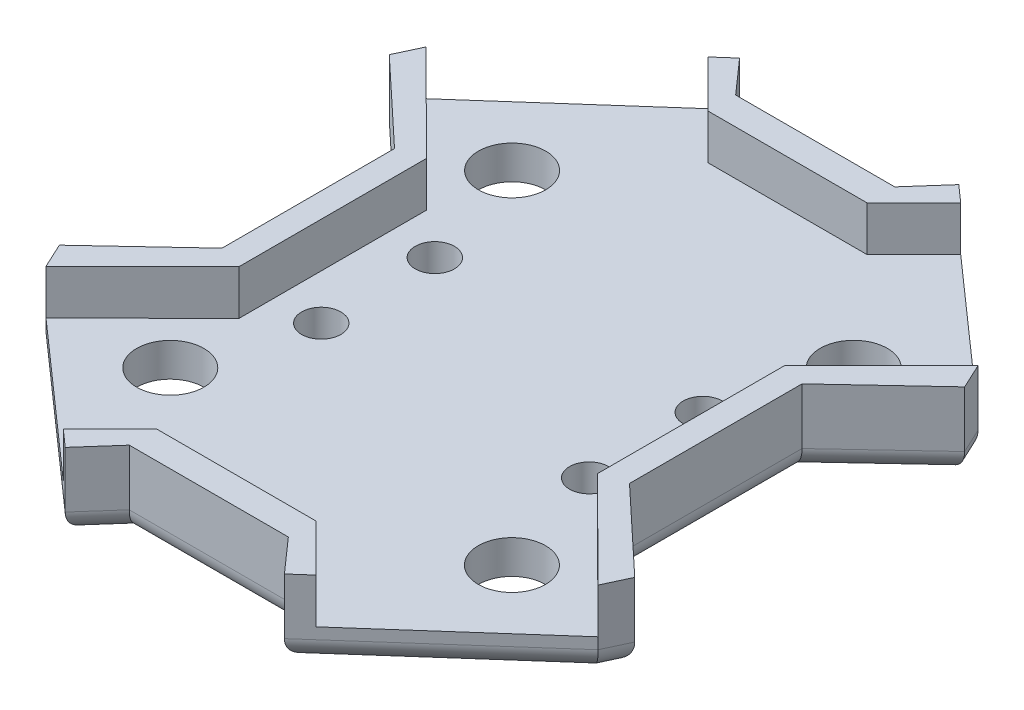
SolidWorks part; units mm, degrees
material "ABS"
ref_plane "Front Plane" through (0, 0, 0) normal (0, 0, 1) x (1, 0, 0)
ref_plane "Top Plane" through (0, 0, 0) normal (0, 1, 0) x (1, 0, 0)
ref_plane "Right Plane" through (0, 0, 0) normal (1, 0, 0) x (0, 0, -1)
sketch "Sketch1" plane through (0, 0, 0) normal (0, 1, 0) x (1, 0, 0)
  line L1 (27.5, -32.215) -> (-27.5, -32.215)
  line L2 (27.5, -32.215) -> (27.5, 32.215)
  line L3 (27.5, 32.215) -> (-27.5, 32.215)
  line L4 (-27.5, -32.215) -> (-27.5, 32.215)
  line L5 (27.5, -32.215) -> (-27.5, 32.215) construction
  line L6 (27.5, 32.215) -> (-27.5, -32.215) construction
  point P0 (0, 0)
  dimension "D1" = 64.43
  dimension "D2" = 55
extrude "Boss-Extrude1" add sketch "Sketch1" along normal blind 3
sketch "Sketch2" plane through (0, 3, 0) normal (0, 1, 0) x (1, 0, 0)
  line L0 (-27.5, -32.215) -> (-27.5, 0) construction
  line L1 (-27.5, 32.215) -> (-27.5, -32.215) construction
  line L2 (-27.5, -32.215) -> (0, -32.215) construction
  line L3 (-27.5, -32.215) -> (27.5, -32.215) construction
  line L4 (-27.5, -4.7913) -> (-27.5, -14.3738)
  line L5 (-27.5, 0) -> (-17.5, 0) construction
  line L6 (-27.5, 4.7913) -> (-27.5, -4.7913)
  line L8 (-17.5, 5) -> (-17.5, -5)
  line L9 (-27.5, -14.3738) -> (-17.5, -5)
  line L10 (0, -32.215) -> (0, 32.215) construction
  line L11 (27.5, 32.215) -> (-27.5, 32.215) construction
  line L12 (-27.5, 14.3738) -> (-17.5, 5)
  line L13 (-27.5, 4.7913) -> (-27.5, 14.3738)
  line L14 (27.5, 4.7913) -> (27.5, 14.3738)
  line L15 (27.5, 14.3738) -> (17.5, 5)
  line L16 (27.5, 4.7913) -> (27.5, -4.7913)
  line L17 (27.5, 0) -> (17.5, 0) construction
  line L18 (17.5, 5) -> (17.5, -5)
  line L19 (27.5, -14.3738) -> (17.5, -5)
  line L20 (27.5, -4.7913) -> (27.5, -14.3738)
  dimension "D1" = 10
  dimension "D2" = 5
extrude "Cut-Extrude1" cut sketch "Sketch2" against normal blind 4
sketch "Sketch3" plane through (0, 3, 0) normal (0, 1, 0) x (1, 0, 0)
  line L0 (-27.5, 14.3738) -> (27.5, 14.3738) construction
  line L1 (0, -32.215) -> (0, 32.215) construction
  line L2 (-27.5, -32.215) -> (27.5, -32.215) construction
  line L3 (27.5, 32.215) -> (-27.5, 32.215) construction
  line L4 (-17.5, 0) -> (17.5, 0) construction
  line L5 (-17.5, -5) -> (-17.5, 5) construction
  line L6 (17.5, 5) -> (17.5, -5) construction
  line L7 (-27.5, 14.3738) -> (-25.8679, 17.8738)
  line L8 (-17.5, 5) -> (-17.5, 0)
  line L9 (-25.8679, 17.8738) -> (27.5, 17.8738) construction
  line L10 (27.5, 14.3738) -> (27.5, 32.215) construction
  line L11 (-25.8679, 17.8738) -> (-25.8679, 32.215) construction
  line L12 (-25.8679, 17.8738) -> (-9.6529, 32.215)
  line L13 (-9.6529, 32.215) -> (-3.7424, 25.5322)
  line L14 (-3.7424, 25.5322) -> (3.7424, 25.5322)
  line L15 (9.6529, 32.215) -> (3.7424, 25.5322)
  line L16 (25.8679, 17.8738) -> (9.6529, 32.215)
  line L17 (27.5, 14.3738) -> (25.8679, 17.8738)
  line L27 (-17.5, 5) -> (-27.5, 14.3738)
  line L30 (17.5, 5) -> (27.5, 14.3738)
  line L31 (17.5, 5) -> (17.5, -5)
  line L32 (17.5, -5) -> (27.5, -14.3738)
  line L33 (27.5, -14.3738) -> (25.8679, -17.8738)
  line L34 (25.8679, -17.8738) -> (9.6529, -32.215)
  line L35 (9.6529, -32.215) -> (3.7424, -25.5322)
  line L36 (-3.7424, -25.5322) -> (3.7424, -25.5322)
  line L37 (-9.6529, -32.215) -> (-3.7424, -25.5322)
  line L38 (-25.8679, -17.8738) -> (-9.6529, -32.215)
  line L39 (-27.5, -14.3738) -> (-25.8679, -17.8738)
  line L40 (-17.5, -5) -> (-27.5, -14.3738)
  line L41 (-17.5, -5) -> (-17.5, 0)
  line L42 (-16, -5.6499) -> (-16, 0)
  line L43 (-16, 5.6499) -> (-16, 0)
  line L44 (-16, 5.6499) -> (-25.6812, 14.7249)
  line L45 (-25.6812, 14.7249) -> (-24.6404, 16.957)
  line L46 (-24.6404, 16.957) -> (-9.7828, 30.0977)
  line L47 (-9.7828, 30.0977) -> (-4.4183, 24.0322)
  line L48 (-4.4183, 24.0322) -> (4.4183, 24.0322)
  line L49 (9.7828, 30.0977) -> (4.4183, 24.0322)
  line L50 (24.6404, 16.957) -> (9.7828, 30.0977)
  line L51 (25.6812, 14.7249) -> (24.6404, 16.957)
  line L52 (16, 5.6499) -> (25.6812, 14.7249)
  line L53 (16, 5.6499) -> (16, -5.6499)
  line L54 (16, -5.6499) -> (25.6812, -14.7249)
  line L55 (25.6812, -14.7249) -> (24.6404, -16.957)
  line L56 (24.6404, -16.957) -> (9.7828, -30.0977)
  line L57 (9.7828, -30.0977) -> (4.4183, -24.0322)
  line L58 (-4.4183, -24.0322) -> (4.4183, -24.0322)
  line L59 (-9.7828, -30.0977) -> (-4.4183, -24.0322)
  line L60 (-24.6404, -16.957) -> (-9.7828, -30.0977)
  line L61 (-25.6812, -14.7249) -> (-24.6404, -16.957)
  line L62 (-16, -5.6499) -> (-25.6812, -14.7249)
  point P27 (0, 23.6915)
  dimension "D1" = 1.5
  dimension "D2" = 3.5
extrude "Cut-Extrude4" cut sketch "Sketch3" against normal blind 4 flip side to cut contours L42 L43 L44 L45 L46 L47 L48 L49 L50 L51 L52 L53 L54 L55 L56 L57 L58 L59 L60 L61 L62
sketch "Sketch4" plane through (0, 3, 0) normal (0, 1, 0) x (1, 0, 0)
  line L0 (-7.1005, 27.0649) -> (7.1005, 27.0649)
  line L1 (-9.7828, 30.0977) -> (-4.4183, 24.0322) construction
  line L2 (9.7828, 30.0977) -> (4.4183, 24.0322) construction
  line L3 (-7.1005, -27.0649) -> (7.1005, -27.0649)
  line L4 (-9.7828, -30.0977) -> (-4.4183, -24.0322) construction
  line L5 (9.7828, -30.0977) -> (4.4183, -24.0322) construction
  line L6 (7.1005, -27.0649) -> (4.4183, -24.0322)
  line L7 (4.4183, -24.0322) -> (-4.4183, -24.0322)
  line L8 (-4.4183, -24.0322) -> (-7.1005, -27.0649)
  line L9 (-7.1005, 27.0649) -> (-4.4183, 24.0322)
  line L10 (-4.4183, 24.0322) -> (4.4183, 24.0322)
  line L11 (4.4183, 24.0322) -> (7.1005, 27.0649)
extrude "Boss-Extrude2" add sketch "Sketch4" against normal blind 3
sketch "Sketch5" plane through (0, 3, 0) normal (0, 1, 0) x (1, 0, 0)
  line L0 (-16, 5.6499) -> (-18.1887, 7.7016)
  line L1 (-16, 5.6499) -> (-25.6812, 14.7249) construction
  line L2 (-16, -5.6499) -> (-18.1887, -7.7016)
  line L3 (-16, -5.6499) -> (-25.6812, -14.7249) construction
  line L4 (-18.1887, 7.7016) -> (-18.1887, -7.7016)
  line L5 (-16, 5.6499) -> (-16, -5.6499)
  line L6 (0, 27.0649) -> (0, -27.0649) construction
  line L7 (7.1005, 27.0649) -> (-7.1005, 27.0649) construction
  line L8 (-7.1005, -27.0649) -> (7.1005, -27.0649) construction
  line L9 (16, 5.6499) -> (18.1887, 7.7016)
  line L10 (18.1887, 7.7016) -> (18.1887, -7.7016)
  line L11 (16, -5.6499) -> (18.1887, -7.7016)
  line L12 (16, 5.6499) -> (16, -5.6499)
  dimension "D1" = 3
  dimension "D2" = 3
extrude "Boss-Extrude3" add sketch "Sketch5" against normal blind 3
sketch "Sketch6" plane through (0, 3, 0) normal (0, 1, 0) x (1, 0, 0)
  line L0 (-24.6404, -16.957) -> (-25.6812, -14.7249)
  line L1 (-25.6812, -14.7249) -> (-18.1887, -7.7016)
  line L2 (-18.1887, -7.7016) -> (-18.1887, 7.7016)
  line L3 (-18.1887, 7.7016) -> (-25.6812, 14.7249)
  line L4 (-25.6812, 14.7249) -> (-24.6404, 16.957)
  line L5 (-24.6404, 16.957) -> (-16, 8.3734)
  line L6 (-16, 8.3734) -> (-16, -8.3734)
  line L7 (-16, -8.3734) -> (-24.6404, -16.957)
  line L8 (-18.1887, 7.7016) -> (-18.1887, -7.7016) construction
  line L9 (0, 27.0649) -> (0, -27.0649) construction
  line L10 (7.1005, 27.0649) -> (-7.1005, 27.0649) construction
  line L11 (-7.1005, -27.0649) -> (7.1005, -27.0649) construction
  line L12 (16, -8.3734) -> (24.6404, -16.957)
  line L13 (16, 8.3734) -> (16, -8.3734)
  line L14 (24.6404, 16.957) -> (16, 8.3734)
  line L15 (25.6812, 14.7249) -> (24.6404, 16.957)
  line L16 (18.1887, 7.7016) -> (25.6812, 14.7249)
  line L17 (18.1887, -7.7016) -> (18.1887, 7.7016)
  line L18 (25.6812, -14.7249) -> (18.1887, -7.7016)
  line L19 (24.6404, -16.957) -> (25.6812, -14.7249)
extrude "Boss-Extrude4" add sketch "Sketch6" along normal blind 4
sketch "Sketch7" plane through (0, 3, 0) normal (0, 1, 0) x (1, 0, 0)
  line L1 (-1, 27.0649) -> (-7.1005, 27.0649)
  line L2 (-7.1005, 27.0649) -> (-9.7828, 30.0977)
  line L3 (-9.7828, 30.0977) -> (-11.2809, 28.7727)
  line L4 (-1, 24.5949) -> (-7.1005, 24.5949)
  line L5 (-7.1005, 24.5949) -> (-11.2809, 28.7727)
  line L6 (0, 27.0649) -> (0, -27.0649) construction
  line L7 (7.1005, 27.0649) -> (-7.1005, 27.0649) construction
  line L8 (-7.1005, -27.0649) -> (7.1005, -27.0649) construction
  line L9 (-1, 27.0649) -> (1, 27.0649)
  line L10 (-1, 24.5949) -> (1, 24.5949)
  line L12 (1, 24.5949) -> (7.1005, 24.5949)
  line L13 (7.1005, 24.5949) -> (11.2809, 28.7727)
  line L14 (9.7828, 30.0977) -> (11.2809, 28.7727)
  line L15 (7.1005, 27.0649) -> (9.7828, 30.0977)
  line L16 (1, 27.0649) -> (7.1005, 27.0649)
  line L17 (-18.1887, 0) -> (18.1887, 0) construction
  line L18 (-18.1887, 7.7016) -> (-18.1887, -7.7016) construction
  line L19 (18.1887, -7.7016) -> (18.1887, 7.7016) construction
  line L20 (-1, -27.0649) -> (-7.1005, -27.0649)
  line L21 (-7.1005, -27.0649) -> (-9.7828, -30.0977)
  line L22 (-9.7828, -30.0977) -> (-11.2809, -28.7727)
  line L23 (-7.1005, -24.5949) -> (-11.2809, -28.7727)
  line L24 (-1, -24.5949) -> (-7.1005, -24.5949)
  line L25 (-1, -24.5949) -> (1, -24.5949)
  line L26 (1, -24.5949) -> (7.1005, -24.5949)
  line L27 (7.1005, -24.5949) -> (11.2809, -28.7727)
  line L28 (9.7828, -30.0977) -> (11.2809, -28.7727)
  line L29 (7.1005, -27.0649) -> (9.7828, -30.0977)
  line L30 (1, -27.0649) -> (7.1005, -27.0649)
  line L31 (-1, -27.0649) -> (1, -27.0649)
extrude "Boss-Extrude5" add sketch "Sketch7" along normal blind 4 contours L9 L16 L15 L14 L13 L12 L10 L4 L5 L3 L2 L1 | L20 L21 L22 L23 L24 L25 L26 L27 L28 L29 L30 L31
fillet "Fillet1" radius 2 20 edges at (25.1608, 0, -15.841) (21.935, 0, -11.2133) (18.1887, 0, 0) (21.935, 0, 11.2133) (25.1608, 0, 15.841) (17.2116, 0, 23.5273) (8.4416, 0, 28.5813) (0, 0, 27.0649) (-8.4416, 0, 28.5813) (-17.2116, 0, 23.5273) (-25.1608, 0, 15.841) (-21.935, 0, 11.2133) (-18.1887, 0, 0) (-25.1608, 0, -15.841) (-21.935, 0, -11.2133) (-17.2116, 0, -23.5273) (-8.4416, 0, -28.5813) (0, 0, -27.0649) (8.4416, 0, -28.5813) (17.2116, 0, -23.5273)
sketch "Sketch9" plane through (0, 3, 0) normal (0, 1, 0) x (1, 0, 0)
  line L0 (25.6812, -14.7249) -> (24.6404, -16.957) construction
  line L1 (25.6812, -14.7249) -> (15.2512, -15.2442) construction
  line L3 (15.2512, -15.2442) -> (-15.2488, -15.2442) construction
  line L4 (15.2512, -15.2442) -> (15.2512, 15.2558) construction
  line L5 (15.2512, 15.2558) -> (-15.2488, 15.2558) construction
  line L6 (-15.2488, -15.2442) -> (-15.2488, 15.2558) construction
  circle A0 centre (15.2512, -15.2442) radius 1.75
  circle A1 centre (15.2512, 15.2558) radius 1.75
  circle A2 centre (-15.2488, 15.2558) radius 1.75
  circle A3 centre (-15.2488, -15.2442) radius 1.75
  dimension "D5" = 3.5
  dimension "D6" = 3.5
  dimension "D7" = 3.5
  dimension "D8" = 3.5
  dimension "D1" = 62.15
  dimension "D2" = 10.43
  dimension "D3" = 30.5
  dimension "D4" = 30.5
extrude "Cut-Extrude6" cut sketch "Sketch9" against normal through all
sketch "Sketch10" plane through (0, 0, 0) normal (0, -1, 0) x (1, 0, 0)
  line L0 (-16.1887, 0) -> (16.1887, 0) construction
  line L1 (-16.1887, 8.5681) -> (-16.1887, -8.5681) construction
  line L2 (16.1887, -8.5681) -> (16.1887, 8.5681) construction
  line L3 (0, 25.0649) -> (0, -25.0649) construction
  line L4 (8.0016, 25.0649) -> (-8.0016, 25.0649) construction
  line L5 (-8.0016, -25.0649) -> (8.0016, -25.0649) construction
  circle A0 centre (-15.2488, -15.2558) radius 3
  circle A1 centre (-15.2488, 15.2558) radius 3
  circle A2 centre (15.2488, -15.2558) radius 3
  circle A3 centre (15.2488, 15.2558) radius 3
  dimension "D1" = 6
extrude "Cut-Extrude7" cut sketch "Sketch10" against normal blind 3
sketch "Sketch11" plane through (0, 3, 0) normal (0, 1, 0) x (1, 0, 0)
  line L0 (18.1887, 0) -> (11.9587, 0) construction
  line L1 (18.1887, -7.7016) -> (18.1887, 7.7016) construction
  line L2 (11.9587, 0) -> (11.9587, -5.07) construction
  line L3 (11.9587, 0) -> (11.9587, 5.07) construction
  line L4 (0, -24.5949) -> (0, 24.5949) construction
  line L5 (7.1005, -24.5949) -> (-7.1005, -24.5949) construction
  line L6 (-7.1005, 24.5949) -> (7.1005, 24.5949) construction
  circle A0 centre (11.9587, -5.07) radius 1.75
  circle A1 centre (11.9587, 5.07) radius 1.75
  circle A2 centre (-11.9587, -5.07) radius 1.75
  circle A3 centre (-11.9587, 5.07) radius 1.75
  dimension "D4" = 3.5
  dimension "D5" = 3.5
  dimension "D1" = 6.23
  dimension "D2" = 5.07
  dimension "D3" = 5.07
extrude "Cut-Extrude8" cut sketch "Sketch11" against normal through all
